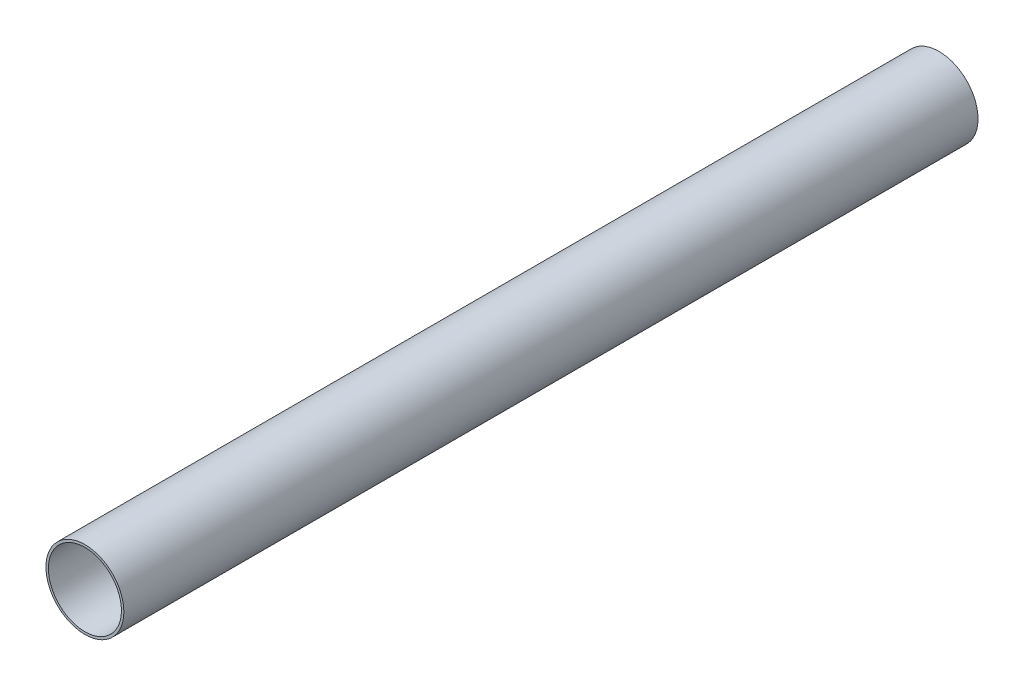
SolidWorks part; units mm, degrees
material "PC High Viscosity"
ref_plane "Front Plane" through (0, 0, 0) normal (0, 0, 1) x (1, 0, 0)
ref_plane "Top Plane" through (0, 0, 0) normal (0, 1, 0) x (1, 0, 0)
ref_plane "Right Plane" through (0, 0, 0) normal (1, 0, 0) x (0, 0, -1)
sketch "Sketch1" plane through (0, 0, 0) normal (0, 0, 1) x (1, 0, 0)
  circle A0 centre (0, 0) radius 23.8125
  circle A1 centre (0, 0) radius 25.4
  dimension "D1" = 50.8
  dimension "D2" = 47.625
extrude "Boss-Extrude1" add sketch "Sketch1" along normal mid plane 556.7505
equation "\"D1@Boss-Extrude1\"=21.125in+3.625mm"
